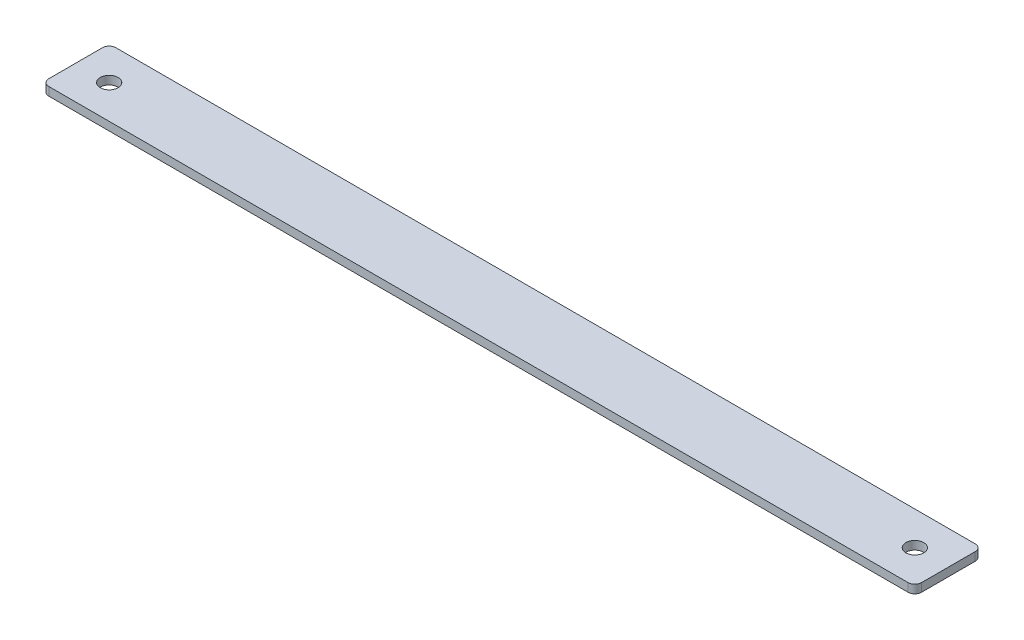
SolidWorks part; units mm, degrees
material "5052-O"
ref_plane "Front Plane" through (0, 0, 0) normal (0, 0, 1) x (1, 0, 0)
ref_plane "Top Plane" through (0, 0, 0) normal (0, 1, 0) x (1, 0, 0)
ref_plane "Right Plane" through (0, 0, 0) normal (1, 0, 0) x (0, 0, -1)
sketch "Sketch2" plane through (0, 0, 0) normal (0, 1, 0) x (1, 0, 0)
  line L0 (-165.1, 0) -> (165.1, 0) construction
  line L1 (-165.1, -12.7) -> (165.1, -12.7)
  line L2 (-165.1, -12.7) -> (-165.1, 12.7)
  line L3 (-165.1, 12.7) -> (165.1, 12.7)
  line L4 (165.1, -12.7) -> (165.1, 12.7)
  line L5 (-165.1, -12.7) -> (165.1, 12.7) construction
  line L6 (-165.1, 12.7) -> (165.1, -12.7) construction
  circle A0 centre (-152.4, 0) radius 3.3734
  circle A1 centre (152.4, 0) radius 3.3734
  point P0 (0, 0)
  dimension "D1" = 6.7469
  dimension "D3" = 6.7469
  dimension "D5" = 12.7
  dimension "D2" = 25.4
  dimension "D4" = 12.7
  dimension "D6" = 304.8
extrude "Boss-Extrude1" add sketch "Sketch2" along normal blind 3.175
fillet "Fillet1" radius 2.54 4 edges at (-165.1, 1.5875, -12.7) (165.1, 1.5875, -12.7) (165.1, 1.5875, 12.7) (-165.1, 1.5875, 12.7)
